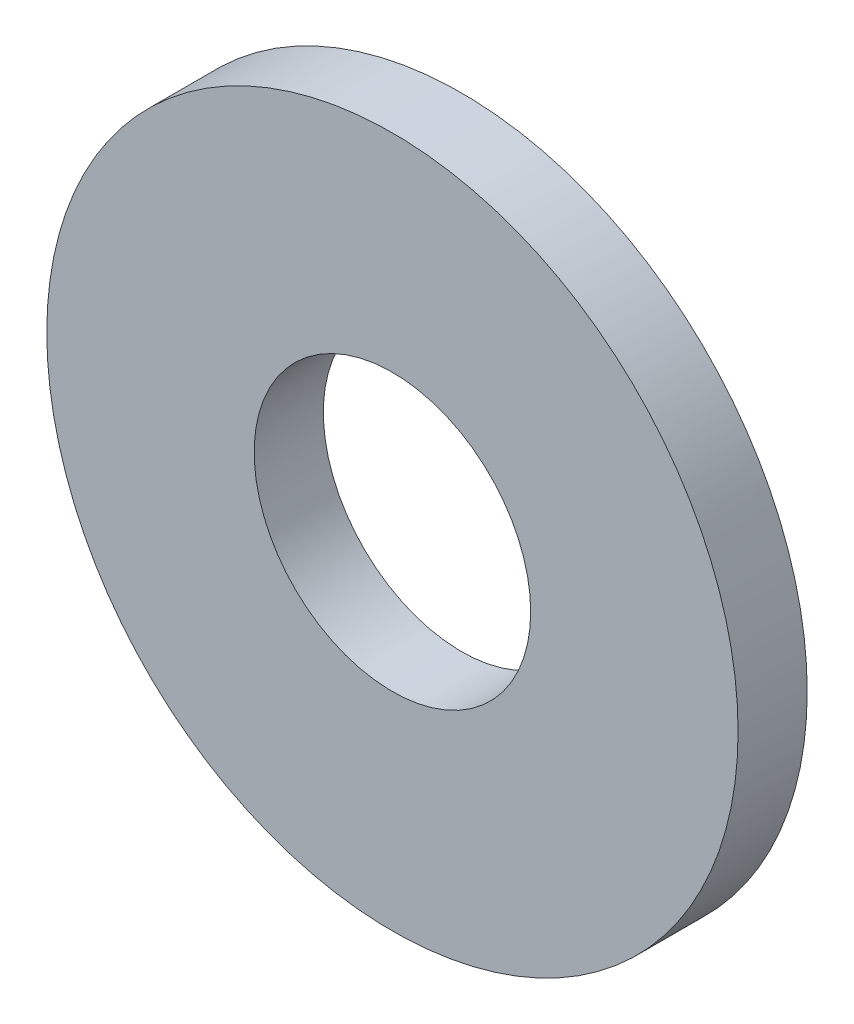
SolidWorks part; units mm, degrees
ref_plane "Front Plane" through (0, 0, 0) normal (0, 0, 1) x (1, 0, 0)
ref_plane "Top Plane" through (0, 0, 0) normal (0, 1, 0) x (1, 0, 0)
ref_plane "Right Plane" through (0, 0, 0) normal (1, 0, 0) x (0, 0, -1)
sketch "Sketch1" plane through (0, 0, 0) normal (0, 0, 1) x (1, 0, 0)
  circle A0 centre (0, 0) radius 7.9375
  circle A1 centre (0, 0) radius 3.175
  dimension "D1" = 15.875
  dimension "D2" = 6.35
extrude "Boss-Extrude1" add sketch "Sketch1" along normal blind 1.5875
